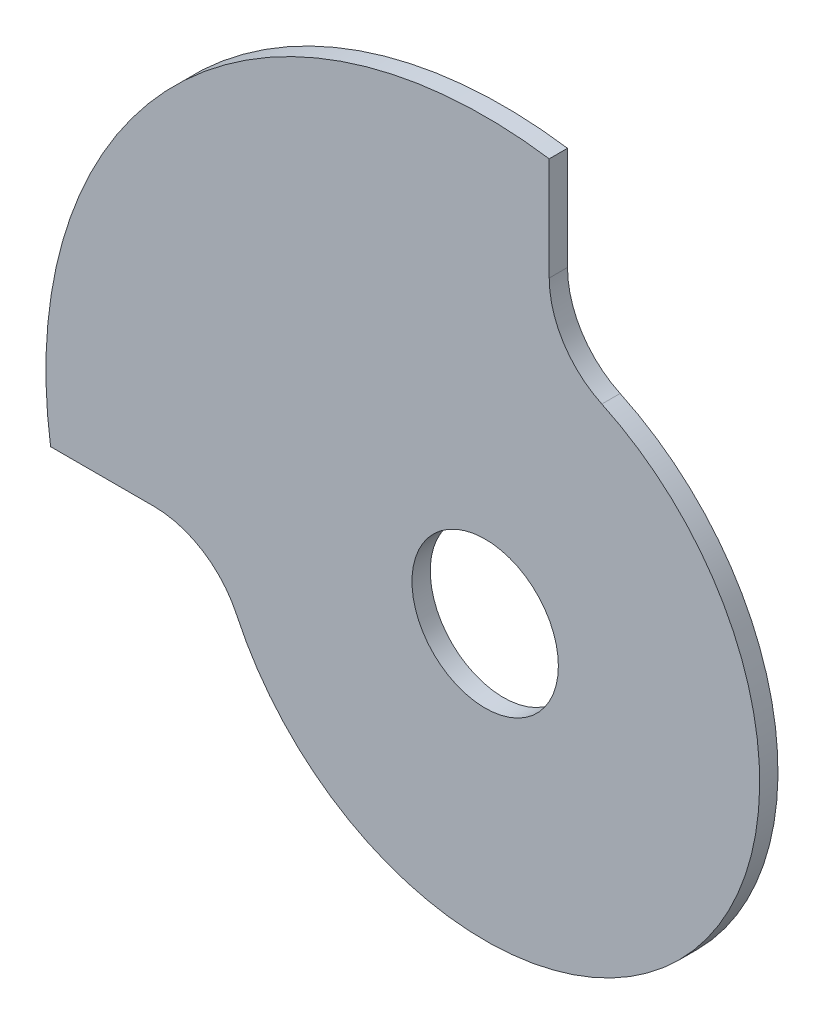
SolidWorks part; units mm, degrees
ref_plane "前视基准面" through (0, 0, 0) normal (0, 0, 1) x (1, 0, 0)
ref_plane "上视基准面" through (0, 0, 0) normal (0, 1, 0) x (1, 0, 0)
ref_plane "右视基准面" through (0, 0, 0) normal (1, 0, 0) x (0, 0, -1)
sketch "草图1" plane through (0, 0, 0) normal (0, 0, 1) x (1, 0, 0)
  circle A0 centre (0, 0) radius 24
  dimension "D1" = 48
extrude "拉伸1" add sketch "草图1" along normal blind 1
sketch "草图2" plane through (0, 0, 1) normal (0, 0, 1) x (1, 0, 0)
  line L0 (-1000, 0) -> (-24, 0) construction
  line L3 (-23.7434, -3.5) -> (-14.586, -3.5)
  line L4 (-15, 0) -> (49000, 0) construction
  line L5 (3.5, 14.586) -> (3.5, 23.7434)
  arc A0 (-14.586, -3.5) -> (3.5, 14.586) centre (0, 0) ccw
  circle A1 centre (0, 0) radius 24 construction
  arc A2 (-23.7434, -3.5) -> (3.5, 23.7434) centre (0, 0) ccw
  circle A3 centre (0, 0) radius 4
  dimension "D1" = 30
  dimension "D2" = 8
  dimension "D3" = 3.5
extrude "切除-拉伸1" cut sketch "草图2" against normal blind 1
fillet "圆角1" radius 5 1 edges at (-14.586, -3.5, 0.5)
fillet "圆角2" radius 5 1 edges at (3.5, 14.586, 0.5)
